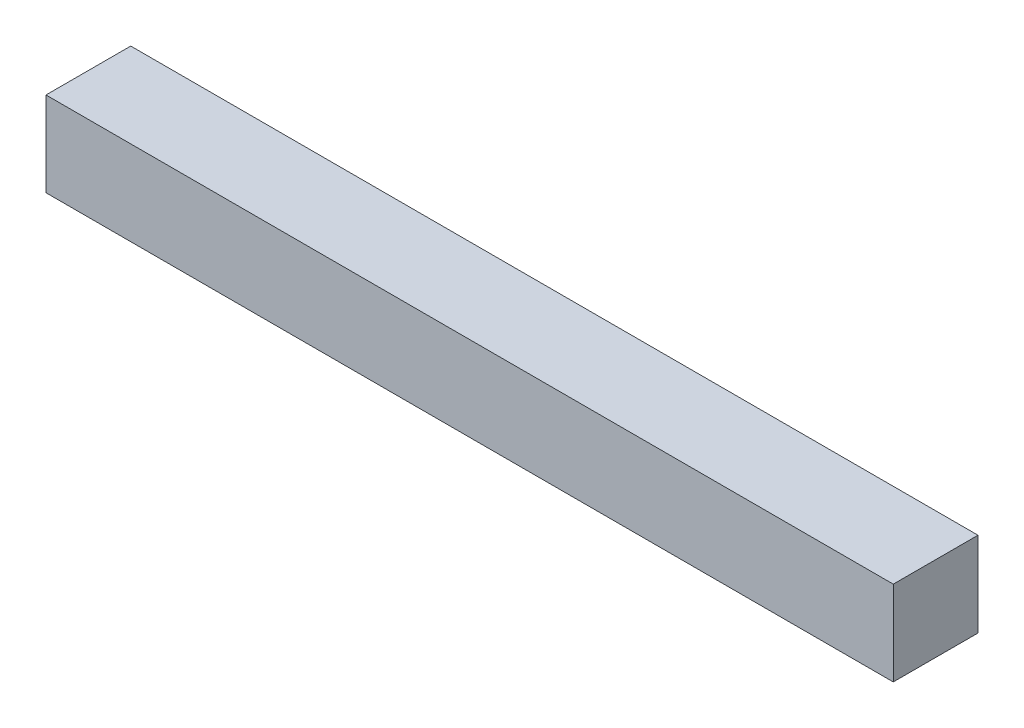
SolidWorks part; units mm, degrees
ref_plane "Front Plane" through (0, 0, 0) normal (0, 0, 1) x (1, 0, 0)
ref_plane "Top Plane" through (0, 0, 0) normal (0, 1, 0) x (1, 0, 0)
ref_plane "Right Plane" through (0, 0, 0) normal (1, 0, 0) x (0, 0, -1)
other "Configuration Table"
sketch "Sketch2" plane through (0, 0, 0) normal (0, 0, 1) x (1, 0, 0)
  line L1 (0, -3.0477) -> (10, -3.0477)
  line L2 (0, -3.0477) -> (0, -2.0477)
  line L3 (0, -2.0477) -> (10, -2.0477)
  line L4 (10, -3.0477) -> (10, -2.0477)
  dimension "D1" = 10
  dimension "D2" = 1
extrude "Extrude1" add sketch "Sketch2" along normal blind 1
